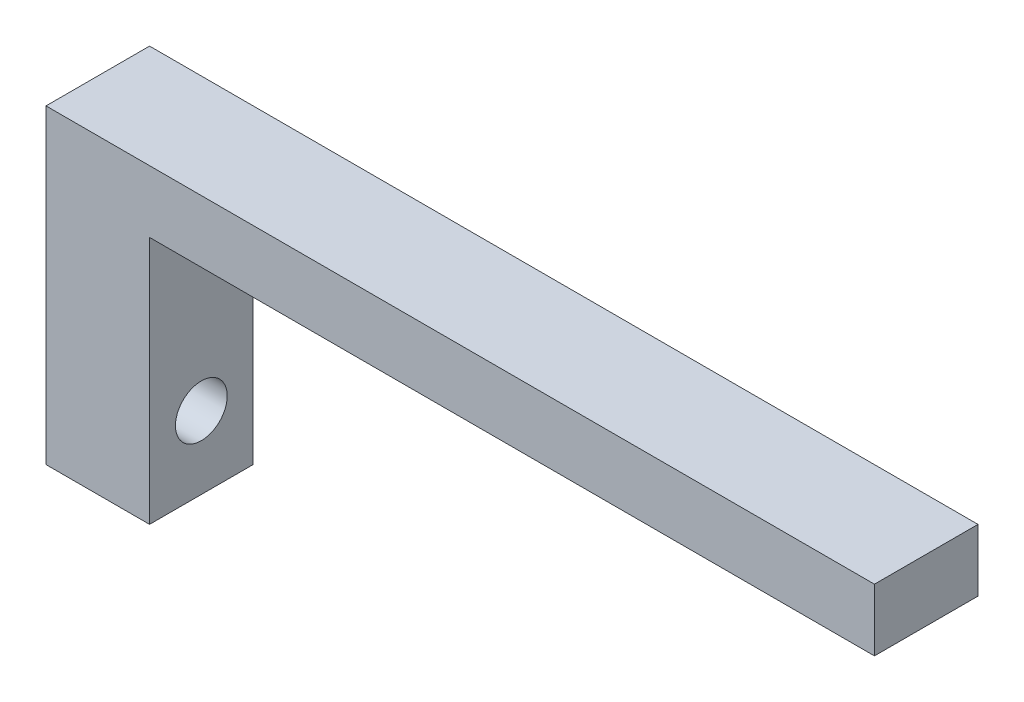
SolidWorks part; units mm, degrees
ref_plane "Front Plane" through (0, 0, 0) normal (0, 0, 1) x (1, 0, 0)
ref_plane "Top Plane" through (0, 0, 0) normal (0, 1, 0) x (1, 0, 0)
ref_plane "Right Plane" through (0, 0, 0) normal (1, 0, 0) x (0, 0, -1)
sketch "Sketch1" plane through (0, 0, 0) normal (0, 0, 1) x (1, 0, 0)
  line L0 (40, 7.5) -> (0, 7.5)
  line L1 (0, 7.5) -> (0, -7.5)
  line L2 (0, -7.5) -> (5, -7.5)
  line L3 (5, -7.5) -> (5, 4.5)
  line L4 (5, 4.5) -> (40, 4.5)
  line L5 (40, 4.5) -> (40, 7.5)
  point P2 (22.2308, 7.5)
  point P9 (0, 0)
  dimension "D1" = 15
  dimension "D2" = 5
  dimension "D3" = 40
  dimension "D4" = 3
extrude "Boss-Extrude1" add sketch "Sketch1" along normal mid plane 5
hole_wizard "M3 Tapped Hole1" positions "Sketch2" profile "Sketch3" tap size "M3" standard "DIN"
sketch "Sketch2" plane through (0, 0, 0) normal (-1, 0, 0) x (0, 0, 1)
  line L0 (0, 7.5) -> (0, 4) construction
  line L1 (2.5, 7.5) -> (-2.5, 7.5) construction
  line L2 (0, 4) -> (0, -4) construction
  line L3 (0, -4) -> (0, -7.5) construction
  line L4 (2.5, -7.5) -> (-2.5, -7.5) construction
  point P0 (0, -4)
  point P2 (0, 4)
  dimension "D1" = 3.5
sketch "Sketch3" plane through (0, -4, 0) normal (0, 1, 0) x (0, 0, 1)
  line L0 (0, 0) -> (0, 14.2511)
  line L1 (0, 14.2511) -> (1.25, 13.5)
  line L2 (1.25, 13.5) -> (1.25, 0)
  line L5 (1.25, 0) -> (0, 0)
  line L10 (0, 14.2511) -> (-1.25, 13.5) construction
  line L11 (0, -6.35) -> (0, 107.95) construction
  dimension "Tap Drill Dia." = 2.5
  dimension "Tap Drill Depth" = 13.5
  dimension "Drill Angle" = 118
